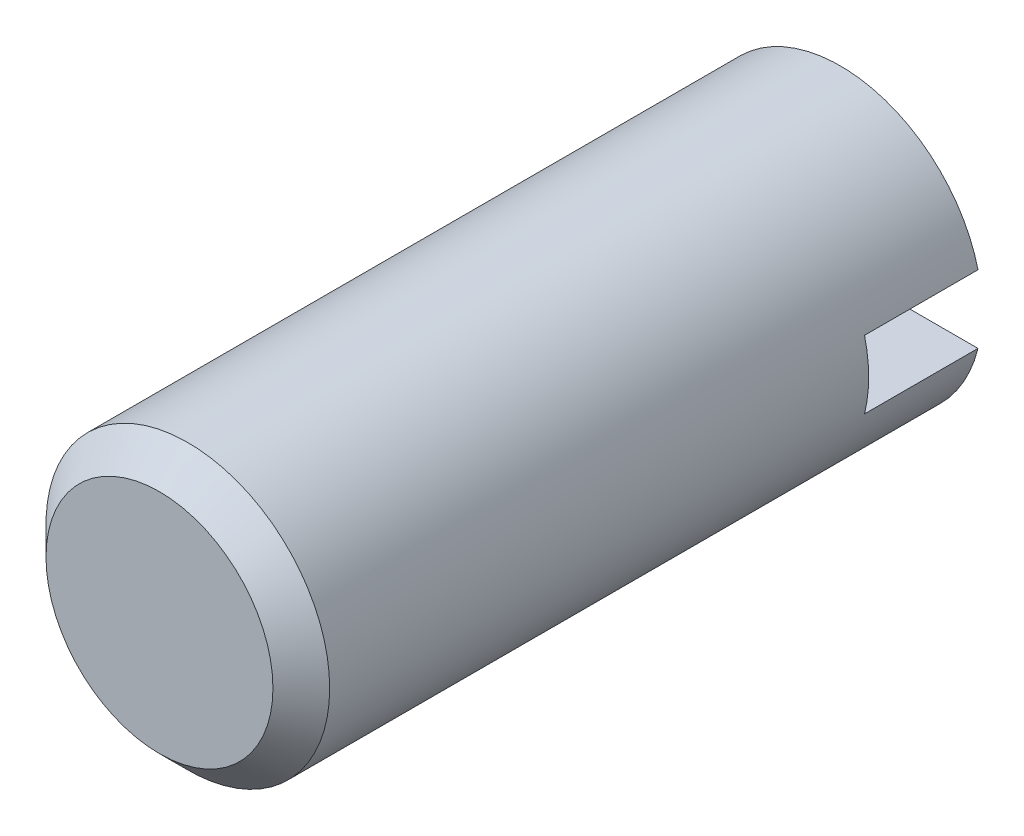
SolidWorks part; units mm, degrees
material "18CrNiMo7-6"
ref_plane "Front Plane" through (0, 0, 0) normal (0, 0, 1) x (1, 0, 0)
ref_plane "Top Plane" through (0, 0, 0) normal (0, 1, 0) x (1, 0, 0)
ref_plane "Right Plane" through (0, 0, 0) normal (1, 0, 0) x (0, 0, -1)
sketch "Sketch1" plane through (0, 0, 0) normal (1, 0, 0) x (0, 0, -1)
  line L0 (0, 0) -> (54.1659, 0) construction
  line L1 (0, 0) -> (0, 2)
  line L2 (0, 2) -> (0.5, 2.5)
  line L3 (0.5, 2.5) -> (12, 2.5)
  line L4 (12, 2.5) -> (12, 0)
  line L5 (0, 0) -> (12, 0)
  dimension "D1" = 5
  dimension "D2" = 0.5
  dimension "D3" = 45
  dimension "D4" = 12
revolve "Revolve1" add sketch "Sketch1" angle 360 about L0
cosmetic thread "Cosmetic Thread1" parameters "D2"=4.2
sketch "Sketch2" plane through (0, 0, -12) normal (0, 0, -1) x (-1, 0, 0)
  line L0 (0, 0) -> (4.1575, 0) construction
  line L1 (-2.7124, 0.6) -> (2.7124, 0.6)
  line L2 (-2.7124, 0.6) -> (-2.7124, -0.6)
  line L3 (-2.7124, -0.6) -> (2.7124, -0.6)
  line L4 (2.7124, 0.6) -> (2.7124, -0.6)
  line L5 (0, 0) -> (0, 1.4043) construction
  dimension "D1" = 5.4248
  dimension "D2" = 1.2
extrude "Cut-Extrude1" cut sketch "Sketch2" against normal blind 2
